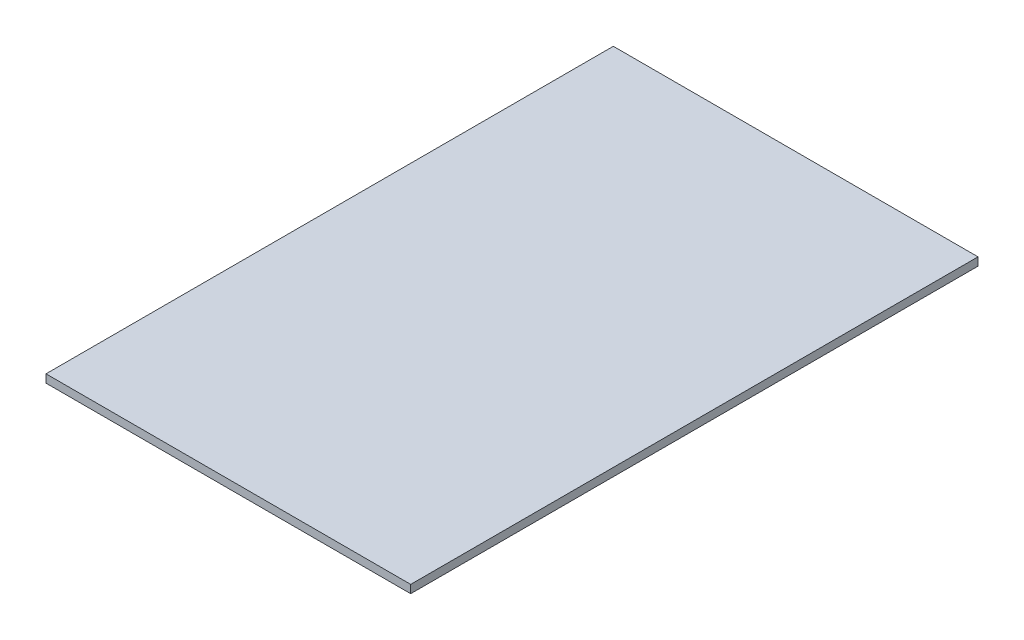
SolidWorks part; units mm, degrees
ref_plane "Front Plane" through (0, 0, 0) normal (0, 0, 1) x (1, 0, 0)
ref_plane "Top Plane" through (0, 0, 0) normal (0, 1, 0) x (1, 0, 0)
ref_plane "Right Plane" through (0, 0, 0) normal (1, 0, 0) x (0, 0, -1)
sketch "Sketch1" plane through (0, 0, 0) normal (0, 1, 0) x (1, 0, 0)
  line L1 (-142.875, -222.25) -> (142.875, -222.25)
  line L2 (-142.875, -222.25) -> (-142.875, 222.25)
  line L3 (-142.875, 222.25) -> (142.875, 222.25)
  line L4 (142.875, -222.25) -> (142.875, 222.25)
  line L5 (-142.875, -222.25) -> (142.875, 222.25) construction
  line L6 (-142.875, 222.25) -> (142.875, -222.25) construction
  point P0 (0, 0)
  dimension "D1" = 285.75
  dimension "D2" = 444.5
extrude "Boss-Extrude1" add sketch "Sketch1" along normal mid plane 6.35
